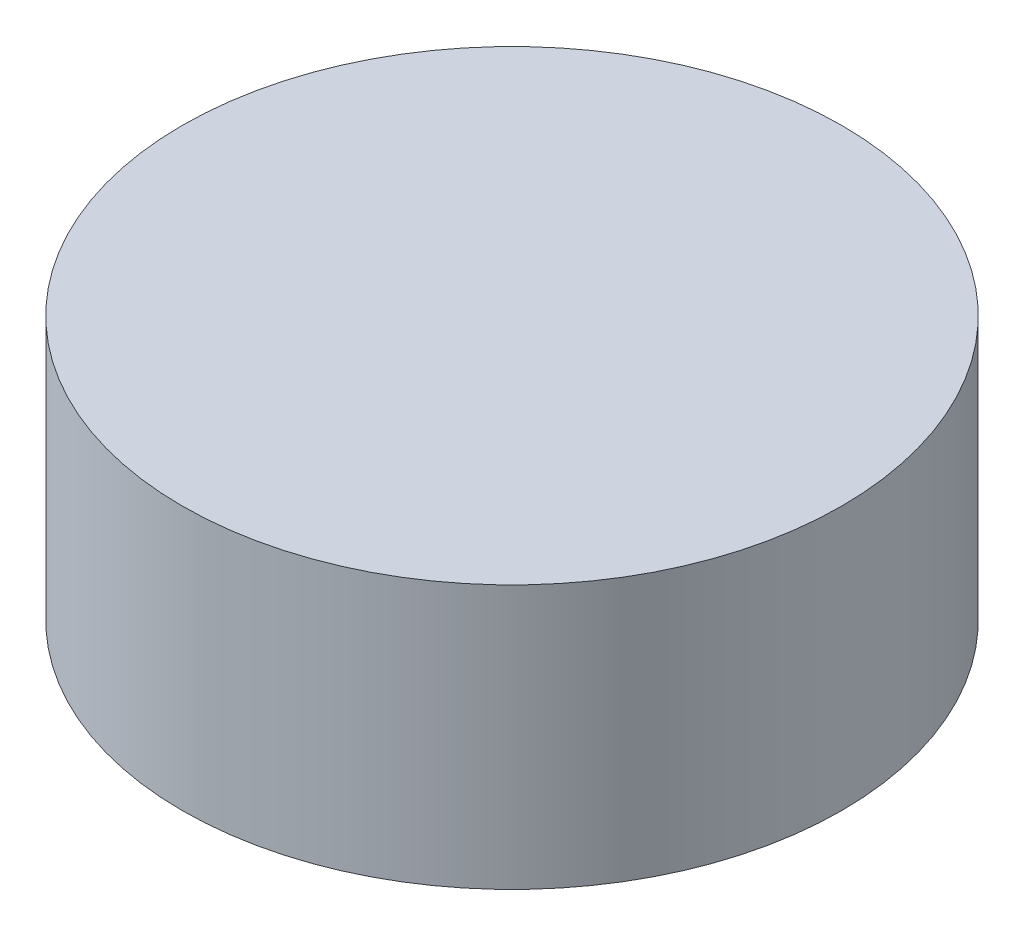
SolidWorks part; units mm, degrees
ref_plane "前视基准面" through (0, 0, 0) normal (0, 0, 1) x (1, 0, 0)
ref_plane "上视基准面" through (0, 0, 0) normal (0, 1, 0) x (1, 0, 0)
ref_plane "右视基准面" through (0, 0, 0) normal (1, 0, 0) x (0, 0, -1)
sketch "草图1" plane through (0, 0, 0) normal (0, 1, 0) x (1, 0, 0)
  circle A0 centre (0, 0) radius 40
  dimension "D1" = 80
extrude "凸台-拉伸1" add sketch "草图1" along normal blind 32
ref_plane "基准面1" through (0, 32, 0) normal (0, 1, 0) x (1, 0, 0)
